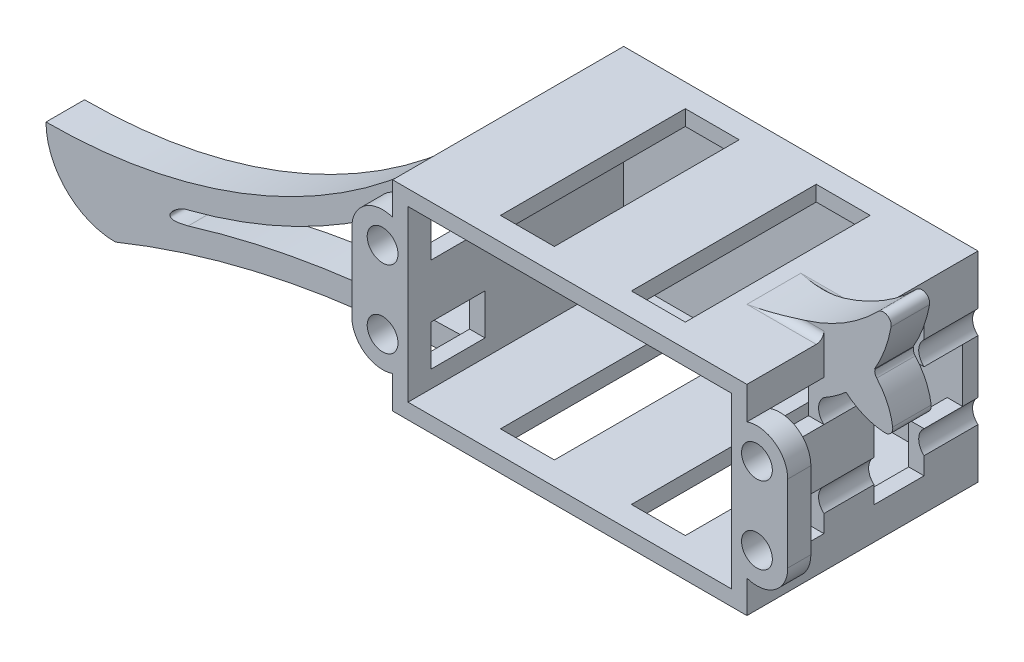
SolidWorks part; units mm, degrees
other "Markup1"
sketch "Sketch15" plane through (31.9332, 19.9963, 30) normal (0.1157, 0.1665, 0.9792) x (0.2474, -0.9596, 0.1339)
other "Markup2"
sketch "Sketch16" plane through (-78, 19.9963, 30) normal (-0.6723, 0.4833, 0.5608) x (0.1241, -0.6733, 0.7289)
material "Custom Plastic"
ref_plane "Front Plane" through (0, 0, 0) normal (0, 0, 1) x (1, 0, 0)
ref_plane "Top Plane" through (0, 0, 0) normal (0, 1, 0) x (1, 0, 0)
ref_plane "Right Plane" through (0, 0, 0) normal (1, 0, 0) x (0, 0, -1)
sketch "Sketch1" plane through (0, 0, 0) normal (0, 0, 1) x (1, 0, 0)
  line L0 (-23, 13) -> (-23, -13)
  line L1 (-20, 10) -> (20, 10) construction
  line L2 (-20, 10) -> (-20, -10) construction
  line L3 (-20, -10) -> (20, -10) construction
  line L4 (20, 10) -> (20, -10) construction
  line L5 (-20, 10) -> (20, -10) construction
  line L6 (-20, -10) -> (20, 10) construction
  line L7 (-23, -13) -> (23, -13)
  line L8 (23, 13) -> (23, -13)
  line L9 (-23, 13) -> (23, 13)
  point P0 (0, 0)
  dimension "D1" = 40
  dimension "D2" = 20
  dimension "D3" = 3
extrude "Boss-Extrude3" add sketch "Sketch1" along normal blind 30
shell "Shell1" thickness 2
sketch "Sketch2" plane through (0, 0, 30) normal (0, 0, 1) x (1, 0, 0)
  line L0 (0, 5) -> (0, -5) construction
  line L1 (-21, 11) -> (21, 11) construction
  line L2 (-21, 11) -> (-21, -11) construction
  line L3 (-21, -11) -> (21, -11) construction
  line L4 (21, 11) -> (21, -11) construction
  line L5 (-24.3, 5) -> (24.3, 5) construction
  line L6 (-24.3, 5) -> (-24.3, -5) construction
  line L7 (-24.3, -5) -> (24.3, -5) construction
  line L8 (24.3, 5) -> (24.3, -5) construction
  line L9 (-24.3, 5) -> (24.3, -5) construction
  line L10 (-24.3, -5) -> (24.3, 5) construction
  line L11 (-24.3, 0) -> (24.3, 0) construction
  line L13 (-28.3, 9) -> (28.3, 9)
  line L14 (-28.3, 9) -> (-28.3, -9)
  line L15 (-28.3, -9) -> (28.3, -9)
  line L16 (28.3, 9) -> (28.3, -9)
  line L17 (-28.3, 9) -> (28.3, -9) construction
  line L18 (-28.3, -9) -> (28.3, 9) construction
  circle A0 centre (-24.3, 5) radius 2
  circle A1 centre (24.3, 5) radius 2
  circle A2 centre (24.3, -5) radius 2
  circle A3 centre (-24.3, -5) radius 2
  circle A4 centre (-24.3, 5) radius 4
  circle A5 centre (-24.3, -5) radius 4
  circle A6 centre (24.3, 5) radius 4
  circle A7 centre (24.3, -5) radius 4
  point P6 (0, 0)
  point P28 (0, 0)
  line M7 (-23, 13) -> (-23, -13)
  line M9 (23, -13) -> (23, 13)
  dimension "D3" = 4
  dimension "D1" = 10
  dimension "D2" = 48.6
  dimension "D4" = 2
  dimension "D5" = 2
  dimension "D6" = 2
  dimension "D7" = 2
sketch "Sketch4" plane through (0, 0, 0) normal (0, 0, 1) x (1, 0, 0)
  line L0 (0, 5) -> (0, -5) construction
  line L1 (-20, 10) -> (20, 10) construction
  line L2 (-20, 10) -> (-20, -10) construction
  line L3 (-20, -10) -> (20, -10) construction
  line L4 (20, 10) -> (20, -10) construction
  line L5 (-24.3, 5) -> (24.3, 5) construction
  line L6 (-24.3, 5) -> (-24.3, -5) construction
  line L7 (-24.3, -5) -> (24.3, -5) construction
  line L8 (24.3, 5) -> (24.3, -5) construction
  line L9 (-24.3, 5) -> (24.3, -5) construction
  line L10 (-24.3, -5) -> (24.3, 5) construction
  line L11 (-24.3, 0) -> (24.3, 0) construction
  line L13 (-28.3, 9) -> (28.3, 9)
  line L14 (-28.3, 9) -> (-28.3, -9)
  line L15 (-28.3, -9) -> (28.3, -9)
  line L16 (28.3, 9) -> (28.3, -9)
  line L17 (-28.3, 9) -> (28.3, -9) construction
  line L18 (-28.3, -9) -> (28.3, 9) construction
  circle A0 centre (-24.3, 5) radius 2
  circle A1 centre (24.3, 5) radius 2
  circle A2 centre (24.3, -5) radius 2
  circle A3 centre (-24.3, -5) radius 2
  circle A4 centre (-24.3, 5) radius 4
  circle A5 centre (-24.3, -5) radius 4
  circle A6 centre (24.3, 5) radius 4
  circle A7 centre (24.3, -5) radius 4
  point P6 (0, 0)
  point P28 (0, 0)
  dimension "D3" = 4
  dimension "D1" = 10
  dimension "D2" = 48.6
  dimension "D4" = 2
  dimension "D5" = 2
  dimension "D6" = 2
  dimension "D7" = 2
extrude "Cut-Extrude2" cut sketch "Sketch4" along normal through all contours A1 | A2 | A0 | A3
extrude "Boss-Extrude4" add sketch "Sketch2" against normal blind 3 contours A6 A1 M9 | A7 L16 A6 M9 | A7 A2 M9 | A4 A0 M7 | L14 A5 A4 M7 | A5 A3 M7
sketch "Sketch5" plane through (23, 0, 0) normal (1, 0, 0) x (0, 0, -1)
  line L0 (-27, 8.7829) -> (0, 8.7829)
  line L1 (0, 6.5199) -> (0, 13) construction
  line L2 (-27, 8.7829) -> (-27, -8.7829)
  line L3 (-27, -8.7829) -> (0, -8.7829)
  line L4 (0, -13) -> (0, -6.5199) construction
  line L5 (0, -8.7829) -> (0, 8.7829)
  line L6 (-20, 8.7829) -> (-20, -8.7829)
  line L7 (-13.5, 8.7829) -> (-13.5, -8.7829) construction
  line L8 (-7, 8.7829) -> (-7, -8.7829)
  line L9 (-7, 3.4801) -> (0, 3.4801)
  line L10 (0, 3.4801) -> (-27, 3.4801) construction
  line L11 (0, 3.4801) -> (0, -3.4801)
  line L12 (0, -3.4801) -> (-7, -3.4801)
  line L13 (0, -3.4801) -> (-27, -3.4801) construction
  line L14 (-2, 3.4801) -> (-2, -3.4801)
  line L15 (-20, 3.4801) -> (-27, 3.4801)
  line L16 (-20, -3.4801) -> (-27, -3.4801)
  line M8 (-27, 8.7829) -> (-27, 6.5199)
  line M9 (-27, 6.5199) -> (0, 6.5199)
  dimension "D1" = 7
  dimension "D2" = 2
extrude "Cut-Extrude4" cut sketch "Sketch5" against normal through all contours L6 L0 M8 M9 | L15 L6 L2 M9 | L6 L16 L2 L3 | L0 L7 L8 M9 | L7 L3 L8 M9 | L14 L9 L8 L12
sketch "Sketch6" plane through (0, 13, 0) normal (0, 1, 0) x (1, 0, 0)
  line L0 (-23, -30) -> (-23, 0)
  line L1 (-23, 0) -> (23, 0)
  line L2 (23, 0) -> (23, -30)
  line L3 (23, -30) -> (23, 0) construction
  line L4 (23, -30) -> (-23, -30) construction
  line L5 (23, -30) -> (-23, -30)
  line L6 (20, -27) -> (-20, -27)
  line L7 (-20, -27) -> (-20, -3)
  line L8 (-20, -3) -> (20, -3)
  line L9 (20, -3) -> (20, -27)
  line L10 (12, -27) -> (12, -3)
  line L11 (5, -27) -> (5, -3)
  line L12 (0, -27) -> (0, -3) construction
  line L13 (-12, -27) -> (-12, -3)
  line L14 (-5, -27) -> (-5, -3)
  dimension "D2" = 7
  dimension "D3" = 5
  dimension "D1" = 3
extrude "Cut-Extrude6" cut sketch "Sketch6" against normal through all contours L11 L6 L10 L8 | L6 L14 L8 L13
sketch "Sketch7" plane through (-23, 0, 0) normal (-1, 0, 0) x (0, 0, 1)
  line L0 (30, -13) -> (0, -13) construction
  line L7 (0, -13) -> (27, -13)
  line L18 (20, -8.7829) -> (0, -8.7829)
  line L19 (20, -8.7829) -> (20, 6.5199)
  line L20 (20, 6.5199) -> (0, 6.5199)
  line L21 (0, -8.7829) -> (0, 6.5199)
  line L22 (27, -8.7829) -> (7, -8.7829)
  line L23 (27, -8.7829) -> (27, 8.7829)
  line L24 (27, 8.7829) -> (7, 8.7829)
  line L25 (7, -8.7829) -> (7, 8.7829)
  line M5 (7, 6.5199) -> (7, 8.7829)
  line M6 (7, 8.7829) -> (13.5, 8.7829)
  line M7 (13.5, 8.7829) -> (13.5, 6.5199)
  line M8 (13.5, 6.5199) -> (20, 6.5199)
  line M9 (20, 6.5199) -> (20, 8.7829)
  line M15 (0, 6.5199) -> (7, 6.5199)
extrude "Boss-Extrude13" add sketch "Sketch7" against normal up to surface (2 mm away) contours L24 M9 M7 M8 | L20 M7 M6 M5 | L25 L18 L19 L20 M8 | L18 L25 L21 M15 up to face at (-21, 6.1315, 23.5)
sketch "Sketch9" plane through (0, 0, 0) normal (0, 0, 1) x (1, 0, 0)
  line L0 (0, 5) -> (0, -5) construction
  line L1 (-20, 10) -> (20, 10) construction
  line L2 (-20, 10) -> (-20, -10) construction
  line L3 (-20, -10) -> (20, -10) construction
  line L4 (20, 10) -> (20, -10) construction
  line L5 (-24.3, 5) -> (24.3, 5) construction
  line L6 (-24.3, 5) -> (-24.3, -5) construction
  line L7 (-24.3, -5) -> (24.3, -5) construction
  line L8 (24.3, 5) -> (24.3, -5) construction
  line L9 (-24.3, 5) -> (24.3, -5) construction
  line L10 (-24.3, -5) -> (24.3, 5) construction
  line L11 (-24.3, 0) -> (24.3, 0) construction
  line L12 (-24.3, 5) -> (-24.3, -5)
  line L13 (-28.3, 9) -> (28.3, 9)
  line L14 (-28.3, 9) -> (-28.3, -9)
  line L15 (-28.3, -9) -> (28.3, -9)
  line L16 (28.3, 9) -> (28.3, -9)
  line L17 (-28.3, 9) -> (28.3, -9) construction
  line L18 (-28.3, -9) -> (28.3, 9) construction
  line L19 (-24.3, 5) -> (10.5, 5)
  line L20 (-24.3, -5) -> (10.5, -5)
  line L21 (10.5, 5) -> (10.5, -5)
  circle A0 centre (-24.3, 5) radius 2
  circle A1 centre (24.3, 5) radius 2
  circle A2 centre (24.3, -5) radius 2
  circle A3 centre (-24.3, -5) radius 2
  circle A4 centre (-24.3, 5) radius 4
  circle A5 centre (-24.3, -5) radius 4
  circle A6 centre (24.3, 5) radius 4
  circle A7 centre (24.3, -5) radius 4
  circle A8 centre (10.5, 0) radius 4.5
  point P6 (0, 0)
  point P28 (0, 0)
  dimension "D3" = 4
  dimension "D9" = 9
  dimension "D1" = 10
  dimension "D2" = 48.6
  dimension "D8" = 34.8
  dimension "D4" = 2
  dimension "D5" = 2
  dimension "D6" = 2
  dimension "D7" = 2
extrude "Boss-Extrude16" add sketch "Sketch9" against normal blind 5 contours L21 A8 | L21 A8
sketch "Sketch14" plane through (0, 0, 0) normal (0, 0, -1) x (-1, 0, 0)
  line L0 (69, 39) -> (69, -13)
  line L1 (-23, 13) -> (69, 13)
  line L2 (-23, 39) -> (-23, -13)
  line L3 (-23, -13) -> (69, -13) construction
  line L4 (23, 39) -> (23, -13)
  line L5 (-115, 39) -> (69, 39)
  line L6 (-69, 39) -> (-69, -65)
  line L7 (-23, 13) -> (-115, 13) construction
  line L8 (-115, 39) -> (-115, -65)
  line L9 (-23, -13) -> (-115, -13)
  line L10 (-23, -39) -> (-115, -39)
  line L11 (-23, -39) -> (161, -39)
  line L12 (23, -65) -> (23, -13)
  line L13 (-115, -65) -> (69, -65)
  line L14 (69, -65) -> (69, -13)
  line L15 (-23, -65) -> (-23, -13)
  line L16 (161, 13) -> (69, 13)
  line L17 (161, -13) -> (69, -13) construction
  line L18 (115, 39) -> (115, -13)
  line L19 (115, -65) -> (115, -13)
  line L20 (-14, 13) -> (-14, 22)
  line L21 (69, -13) -> (78, -13) construction
  line L22 (69, -13) -> (69, -22)
  line L23 (69, -22) -> (78, -22)
  line L24 (78, -13) -> (78, -22)
  line L25 (-14, 13) -> (-32, 13) construction
  line L26 (-23, 13) -> (-23, 22)
  line L27 (-14, 22) -> (-32, 22)
  line L28 (-32, 13) -> (-32, 22)
  line L30 (-23, 6.5199) -> (-32, 6.5199)
  line L31 (-23, 6.5199) -> (-23, 13)
  line L32 (-23, 13) -> (-32, 13)
  line L33 (-32, 6.5199) -> (-32, 13)
  line L34 (-23, 6.5199) -> (-21, 6.5199)
  line L35 (-23, 6.5199) -> (-23, 13)
  line L36 (-23, 13) -> (-21, 13)
  line L37 (-21, 6.5199) -> (-21, 13)
  arc A0 (23, -13) -> (69, -22) centre (23, -135.0556) cw
  arc A1 (69, -22) -> (78, -13) centre (69, -13) ccw
  arc A2 (78, -13) -> (23, 13) centre (78, 58.1731) cw
  arc A3 (-14, 13) -> (-30.0176, 19.6985) centre (-14, 35.5) cw
  arc A4 (-31.7134, 18.8176) -> (-29.7214, 13.2831) centre (-14.187, 22) ccw
  arc A5 (-31.9242, 7.6449) -> (-29.85, 12.125) centre (-23.6186, 6.5199) cw
  arc A6 (-23, 14.8784) -> (-30.8725, 6.5125) centre (-31.3814, 14.8784) cw
  arc A7 (-30.0176, 19.6985) -> (-31.7134, 18.8176) centre (-30.7295, 18.9963) ccw
  arc A8 (-29.85, 12.125) -> (-29.7214, 13.2831) centre (-30.5935, 12.7937) ccw
  arc A9 (-31.9242, 7.6449) -> (-30.8725, 6.5125) centre (-30.9332, 7.5106) ccw
  arc A10 (-29.7214, 13.2831) -> (-23, 6.5199) centre (-14.187, 22) ccw
  arc A11 (78, -16) -> (20.6817, 11.0959) centre (78, 58.1731) cw
  arc A12 (23, -10) -> (70.1306, -19.2212) centre (23, -135.0556) cw
  arc A13 (69, -19) -> (75, -13) centre (69, -13) ccw construction
  spline S0 degree 3 poles (59.5435, -15.4585) (63.9567, -16.6758) (61.1597, -13.9287) (59.5435, -13.667) knots 0 0 0 0 1 1 1 1
  point P9 (23, 13)
  point P18 (-69, -13)
  point P25 (69, -39)
  point P30 (78, -13)
  dimension "D5" = 1
  dimension "D1" = 55
  dimension "D2" = 9
  dimension "D3" = 9
  dimension "D4" = 9
  dimension "D6" = 2
  dimension "D7" = 3
extrude "Boss-Extrude18" add sketch "Sketch14" against normal blind 5 from offset 15 offset against normal yes
fillet "Fillet1" radius 1 1 edges at (-23, 8.4072, 17.5)
fillet "Fillet2" radius 1 1 edges at (-23, -10, 17.5)
fillet "Fillet3" radius 1 1 edges at (18.5, 13, 15)
fillet "Fillet4" radius 1 1 edges at (18.5, 13, 20)
